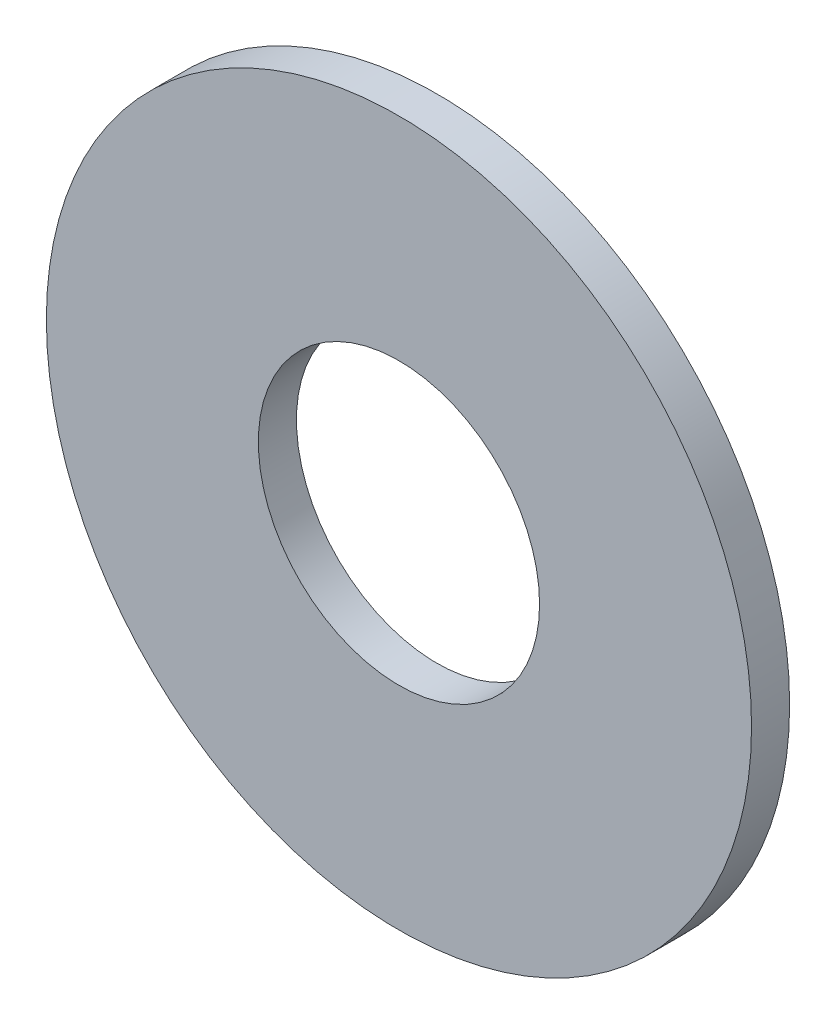
SolidWorks part; units mm, degrees
ref_plane "Front Plane" through (0, 0, 0) normal (0, 0, 1) x (1, 0, 0)
ref_plane "Top Plane" through (0, 0, 0) normal (0, 1, 0) x (1, 0, 0)
ref_plane "Right Plane" through (0, 0, 0) normal (1, 0, 0) x (0, 0, -1)
sketch "Sketch1" plane through (0, 0, 0) normal (0, 0, 1) x (1, 0, 0)
  circle A0 centre (0, 0) radius 58.7797
  circle A1 centre (0, 0) radius 23.4412
extrude "Extrude1" add sketch "Sketch1" along normal blind 6.35
